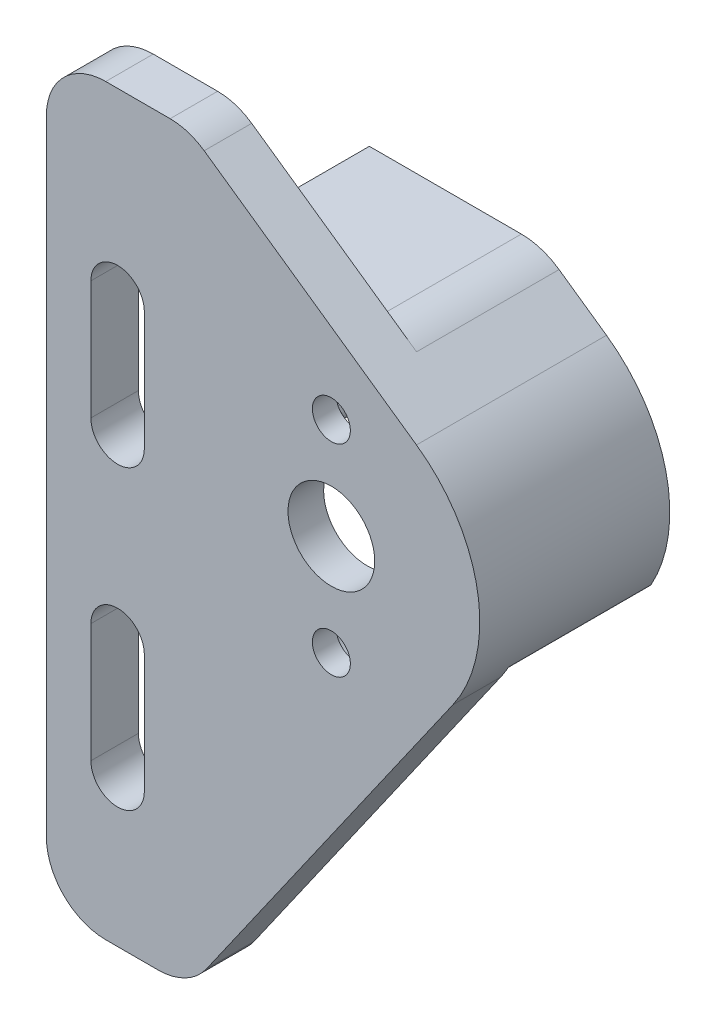
SolidWorks part; units mm, degrees
material "3D printed plastic"
ref_plane "Front Plane" through (0, 0, 0) normal (0, 0, 1) x (1, 0, 0)
ref_plane "Top Plane" through (0, 0, 0) normal (0, 1, 0) x (1, 0, 0)
ref_plane "Right Plane" through (0, 0, 0) normal (1, 0, 0) x (0, 0, -1)
sketch "Sketch1" plane through (0, 0, 0) normal (0, 0, 1) x (1, 0, 0)
  line L0 (-18, 8.5) -> (-18, -1.5) construction
  line L1 (-15.75, 8.5) -> (-15.75, -1.5)
  line L2 (-20.25, 8.5) -> (-20.25, -1.5)
  line L3 (-18, -16.5) -> (-18, -26.5) construction
  line L4 (-15.75, -16.5) -> (-15.75, -26.5)
  line L5 (-20.25, -16.5) -> (-20.25, -26.5)
  line L6 (-18, 3.5) -> (-18, -21.5) construction
  line L7 (-24, 18.6622) -> (-24, -33.9309)
  line L8 (-19, -38.9309) -> (-14.6028, -38.9309)
  line L9 (-10.5071, -36.7987) -> (10.2394, -7.1697)
  line L10 (7.1697, 10.2394) -> (-10.7086, 22.7579)
  line L11 (-13.5765, 23.6622) -> (-19, 23.6622)
  line L12 (0, -8.5) -> (0, 8.5) construction
  circle A0 centre (0, 0) radius 3.65
  arc A1 (10.2394, -7.1697) -> (7.1697, 10.2394) centre (0, 0) ccw
  arc A2 (-15.75, 8.5) -> (-20.25, 8.5) centre (-18, 8.5) ccw
  arc A3 (-20.25, -1.5) -> (-15.75, -1.5) centre (-18, -1.5) ccw
  arc A4 (-15.75, -16.5) -> (-20.25, -16.5) centre (-18, -16.5) ccw
  arc A5 (-20.25, -26.5) -> (-15.75, -26.5) centre (-18, -26.5) ccw
  circle A6 centre (0, 8.5) radius 1.6
  circle A7 centre (0, -8.5) radius 1.6
  arc A8 (-24, -33.9309) -> (-19, -38.9309) centre (-19, -33.9309) ccw
  arc A9 (-24, 18.6622) -> (-19, 23.6622) centre (-19, 18.6622) cw
  arc A10 (-14.6028, -38.9309) -> (-10.5071, -36.7987) centre (-14.6028, -33.9309) ccw
  arc A11 (-10.7086, 22.7579) -> (-13.5765, 23.6622) centre (-13.5765, 18.6622) ccw
  point P6 (-18, 3.5)
  point P12 (-18, -21.5)
  point P31 (-24, -38.9309)
  point P34 (-24, 23.6622)
  point P37 (-12, -38.9309)
  point P40 (-12, 23.6622)
  dimension "D1" = 7.3
  dimension "D2" = 4.5
  dimension "D4" = 10
  dimension "D6" = 25
  dimension "D8" = 55
  dimension "D10" = 35
  dimension "D13" = 17
  dimension "D14" = 3.2
  dimension "D15" = 5
  dimension "D16" = 5
  dimension "D3" = 18
  dimension "D5" = 25
  dimension "D7" = 3.5
  dimension "D9" = 6
  dimension "D11" = 12
  dimension "D12" = 12
extrude "Boss-Extrude1" add sketch "Sketch1" along normal mid plane 4
sketch "Sketch2" plane through (0, 0, -2) normal (0, 0, -1) x (-1, 0, 0)
  circle A0 centre (0, 8.5) radius 3
  circle A1 centre (0, -8.5) radius 3
  dimension "D1" = 6
extrude "Cut-Extrude1" cut sketch "Sketch2" against normal blind 2
sketch "Sketch3" plane through (0, 0, -2) normal (0, 0, -1) x (-1, 0, 0)
  circle A0 centre (0, 0) radius 6
  dimension "D1" = 12
extrude "Cut-Extrude2" cut sketch "Sketch3" against normal blind 1
fillet "Fillet1" radius 1 4 edges at (1.3838, -5.8382, -1.5) (-1.3838, -5.8382, -1.5) (-1.3838, 5.8382, -1.5) (1.3838, 5.8382, -1.5)
sketch "Sketch4" plane through (0, 0, -2) normal (0, 0, -1) x (-1, 0, 0)
  line L0 (-7.1697, 10.2394) -> (10.7086, 22.7579) construction
  line L1 (9.8, 7) -> (1.3572, 11.2171)
  line L2 (-7.1697, 10.2394) -> (-3.176, 13.0358)
  line L3 (12.8, 7) -> (12.8, 14.0372)
  line L4 (12.8, 7) -> (9.8, 7)
  line L5 (-1.7421, 10.9879) -> (-5.7358, 8.1915)
  line L6 (12.8, 14.0372) -> (0, 14.0372)
  line L7 (-5.1729, 11.6376) -> (-3.7389, 9.5897) construction
  line L8 (24, 18.6622) -> (24, -33.9309) construction
  line L9 (-10, 0) -> (-10, -5.8095)
  line L10 (13.5765, 23.6622) -> (19, 23.6622) construction
  arc A0 (-7.1697, 10.2394) -> (-10.2394, -7.1697) centre (0, 0) ccw construction
  arc A1 (-7.1697, 10.2394) -> (-10.9375, -6.0515) centre (0, 0) ccw
  arc A2 (-5.7358, 8.1915) -> (-10, 0) centre (0, 0) ccw
  arc A3 (1.3572, 11.2171) -> (-1.7421, 10.9879) centre (0, 8.5) ccw
  arc A4 (0, 14.0372) -> (-3.176, 13.0358) centre (0, 8.5) ccw
  circle A7 centre (0, 8.5) radius 3 construction
  arc A8 (2.7998, -5.3067) -> (2.7998, 5.3067) centre (0, 0) ccw construction
  arc A9 (-10, -5.8095) -> (-10.9375, -6.0515) centre (-10.5, -5.8095) cw
  dimension "D1" = 2.5
  dimension "D4" = 3
  dimension "D5" = 7
  dimension "D6" = 0.5
  dimension "D2" = 11.2
  dimension "D3" = 0
extrude "Boss-Extrude2" add sketch "Sketch4" along normal blind 12
